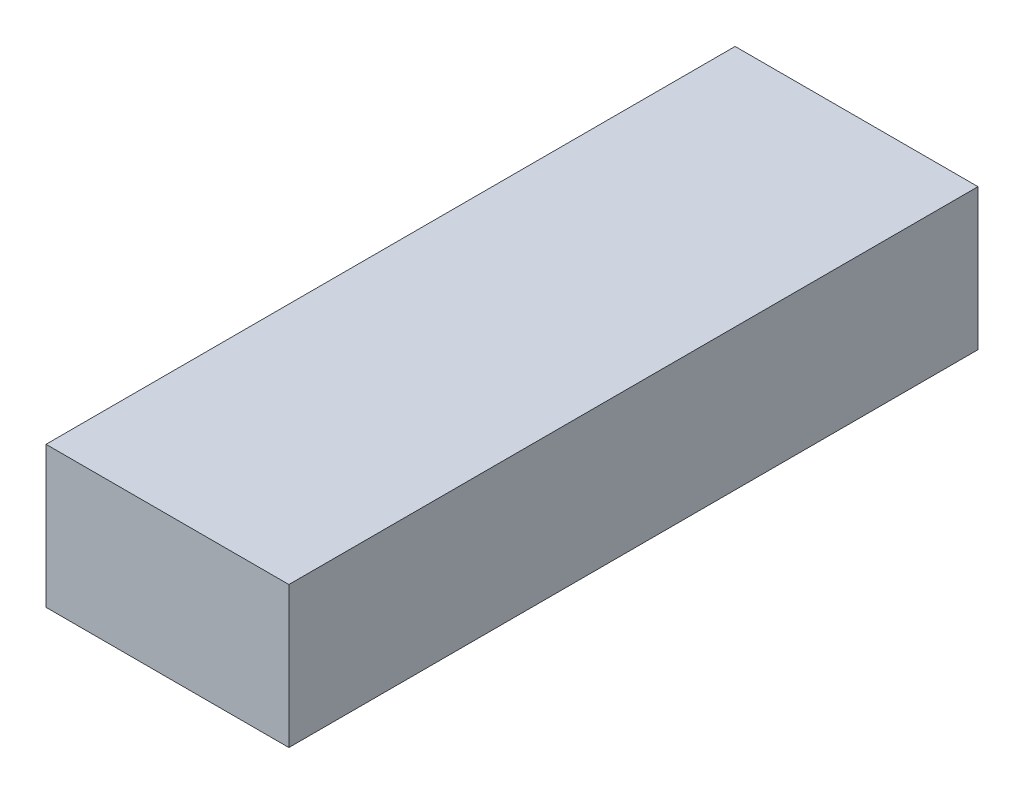
SolidWorks part; units mm, degrees
ref_plane "Front" through (0, 0, 0) normal (0, 0, 1) x (1, 0, 0)
ref_plane "Top" through (0, 0, 0) normal (0, 1, 0) x (1, 0, 0)
ref_plane "Right" through (0, 0, 0) normal (1, 0, 0) x (0, 0, -1)
sketch "Sketch1" plane through (0, 0, 0) normal (0, 0, 1) x (1, 0, 0)
  line L1 (-20.5, 13.5) -> (22.5, 13.5)
  line L2 (-20.5, 13.5) -> (-20.5, -11.5)
  line L3 (-20.5, -11.5) -> (22.5, -11.5)
  line L4 (22.5, 13.5) -> (22.5, -11.5)
  dimension "D1" = 43
  dimension "D2" = 25
  dimension "D3" = 22.5
  dimension "D4" = 13.5
extrude "Extrude1" add sketch "Sketch1" along normal blind 55 and the other way blind 67
